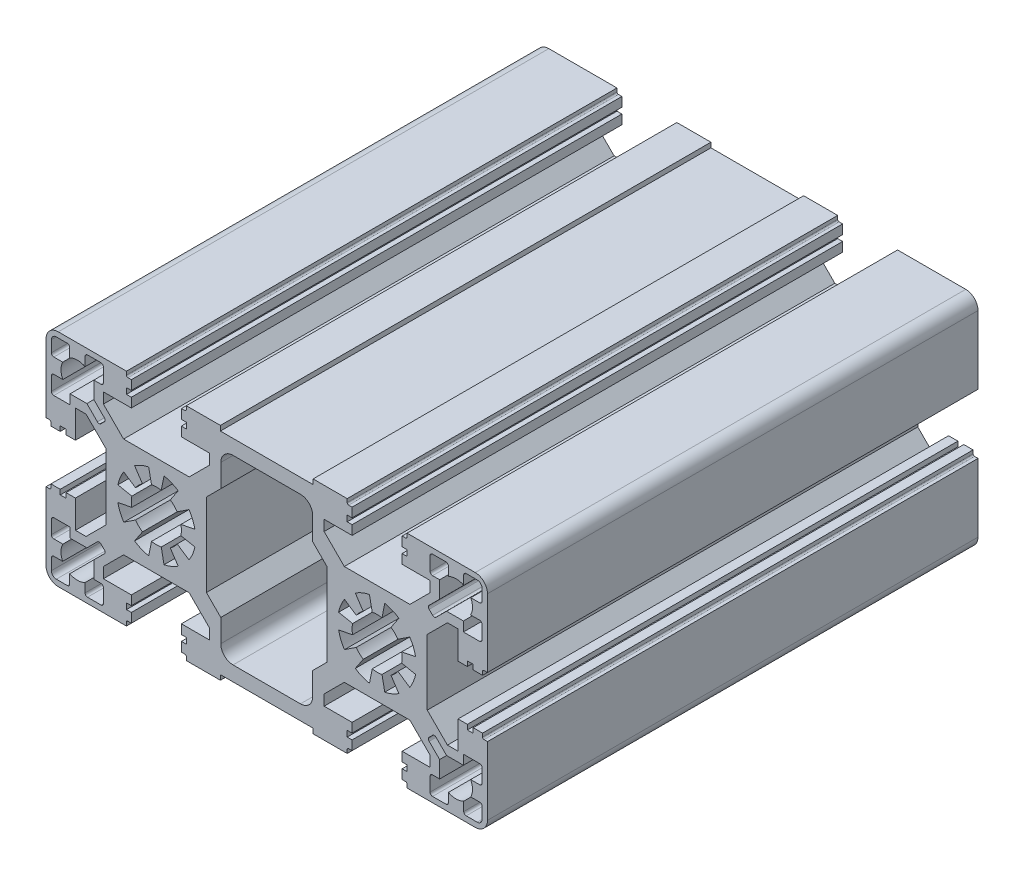
SolidWorks part; units mm, degrees
ref_plane "前视基准面" through (0, 0, 0) normal (0, 0, 1) x (1, 0, 0)
ref_plane "上视基准面" through (0, 0, 0) normal (0, 1, 0) x (1, 0, 0)
ref_plane "右视基准面" through (0, 0, 0) normal (1, 0, 0) x (0, 0, -1)
sketch "草图1" plane through (0, 0, 0) normal (0, 0, 1) x (1, 0, 0)
  line L0 (-29.3856, 22.9542) -> (-43.2856, 22.9542)
  line L1 (-45.7856, 20.4542) -> (-45.7856, 6.5542)
  line L2 (-28.3856, 16.9542) -> (-34.0856, 16.9542)
  line L3 (-39.7856, 11.2542) -> (-39.7856, 5.5542)
  line L4 (-28.3856, 21.9542) -> (-29.0856, 21.9542)
  line L5 (-29.3856, 22.2542) -> (-29.3856, 22.9542)
  line L6 (-45.7856, 6.5542) -> (-45.0856, 6.5542)
  line L7 (-44.7856, 6.2542) -> (-44.7856, 5.5542)
  line L8 (-39.7856, 11.2542) -> (-37.6211, 11.2542)
  line L9 (-42.8856, 6.5542) -> (-41.6856, 6.5542)
  line L10 (-44.7856, 5.5542) -> (-42.8856, 5.5542)
  line L11 (-41.6856, 5.5542) -> (-39.7856, 5.5542)
  line L12 (-34.0856, 16.9542) -> (-34.0856, 14.7897)
  line L13 (-29.3856, 20.0542) -> (-29.3856, 18.8542)
  line L14 (-28.3856, 21.9542) -> (-28.3856, 20.0542)
  line L15 (-28.3856, 18.8542) -> (-28.3856, 16.9542)
  line L16 (-28.3856, 18.8542) -> (-29.3856, 18.8542)
  line L17 (-28.3856, 20.0542) -> (-29.3856, 20.0542)
  line L19 (-41.6856, 5.5542) -> (-41.6856, 6.5542)
  line L20 (-42.8856, 5.5542) -> (-42.8856, 6.5542)
  line L21 (-18.1856, 16.9542) -> (-12.4856, 16.9542)
  line L22 (-18.1856, 21.9542) -> (-17.4856, 21.9542)
  line L23 (-17.1856, 22.2542) -> (-17.1856, 22.9542)
  line L24 (-12.4856, 16.9542) -> (-12.4856, 14.7897)
  line L25 (-17.1856, 20.0542) -> (-17.1856, 18.8542)
  line L26 (-18.1856, 18.8542) -> (-17.1856, 18.8542)
  line L27 (-18.1856, 20.0542) -> (-17.1856, 20.0542)
  line L28 (-18.1856, 21.9542) -> (-18.1856, 20.0542)
  line L29 (-18.1856, 18.8542) -> (-18.1856, 16.9542)
  line L30 (-29.3856, -22.0458) -> (-43.2856, -22.0458)
  line L31 (-45.7856, -19.5458) -> (-45.7856, -5.6458)
  line L32 (-28.3856, -16.0458) -> (-34.0856, -16.0458)
  line L33 (-39.7856, -10.3458) -> (-39.7856, -4.6458)
  line L34 (-28.3856, -21.0458) -> (-29.0856, -21.0458)
  line L35 (-29.3856, -21.3458) -> (-29.3856, -22.0458)
  line L36 (-45.7856, -5.6458) -> (-45.0856, -5.6458)
  line L37 (-44.7856, -5.3458) -> (-44.7856, -4.6458)
  line L38 (-39.7856, -10.3458) -> (-37.6211, -10.3458)
  line L39 (-42.8856, -5.6458) -> (-41.6856, -5.6458)
  line L40 (-44.7856, -4.6458) -> (-42.8856, -4.6458)
  line L41 (-41.6856, -4.6458) -> (-39.7856, -4.6458)
  line L42 (-34.0856, -16.0458) -> (-34.0856, -13.8813)
  line L43 (-29.3856, -19.1458) -> (-29.3856, -17.9458)
  line L44 (-28.3856, -21.0458) -> (-28.3856, -19.1458)
  line L45 (-28.3856, -17.9458) -> (-28.3856, -16.0458)
  line L46 (-28.3856, -17.9458) -> (-29.3856, -17.9458)
  line L47 (-28.3856, -19.1458) -> (-29.3856, -19.1458)
  line L49 (-41.6856, -4.6458) -> (-41.6856, -5.6458)
  line L50 (-42.8856, -4.6458) -> (-42.8856, -5.6458)
  line L51 (-18.1856, -16.0458) -> (-12.4856, -16.0458)
  line L52 (-18.1856, -21.0458) -> (-17.4856, -21.0458)
  line L53 (-17.1856, -21.3458) -> (-17.1856, -22.0458)
  line L54 (-12.4856, -16.0458) -> (-12.4856, -13.8813)
  line L55 (-17.1856, -19.1458) -> (-17.1856, -17.9458)
  line L56 (-18.1856, -17.9458) -> (-17.1856, -17.9458)
  line L57 (-18.1856, -19.1458) -> (-17.1856, -19.1458)
  line L58 (-18.1856, -21.0458) -> (-18.1856, -19.1458)
  line L59 (-18.1856, -17.9458) -> (-18.1856, -16.0458)
  line L60 (-33.5056, 7.1387) -> (-33.5056, -6.2303)
  line L61 (-29.9701, -9.7658) -> (-16.6011, -9.7658)
  line L62 (-16.6011, 10.6742) -> (-29.9701, 10.6742)
  line L63 (-27.7302, -6.1975) -> (-26.119, -3.7863)
  line L64 (-24.8463, -7.3921) -> (-24.2806, -4.5478)
  line L65 (-21.7249, -7.3921) -> (-22.2907, -4.5478)
  line L66 (-18.8411, -6.1975) -> (-20.4522, -3.7863)
  line L67 (-16.6339, -3.9904) -> (-19.0451, -2.3792)
  line L68 (-15.4393, -1.1065) -> (-18.2836, -0.5408)
  line L69 (-15.4393, 2.0149) -> (-18.2836, 1.4492)
  line L70 (-16.6339, 4.8988) -> (-19.0451, 3.2876)
  line L71 (-18.8411, 7.106) -> (-20.4522, 4.6947)
  line L72 (-21.7249, 8.3005) -> (-22.2907, 5.4562)
  line L73 (-24.8463, 8.3005) -> (-24.2806, 5.4562)
  line L74 (-27.7302, 7.106) -> (-26.119, 4.6947)
  line L75 (-29.9374, 4.8988) -> (-27.5261, 3.2876)
  line L76 (-31.1319, 2.0149) -> (-28.2876, 1.4492)
  line L77 (-31.1319, -1.1065) -> (-28.2876, -0.5408)
  line L78 (-29.9374, -3.9904) -> (-27.5261, -2.3792)
  line L79 (-34.0856, 14.7897) -> (-29.9701, 10.6742)
  line L80 (-37.6211, 11.2542) -> (-33.5056, 7.1387)
  line L81 (-12.4856, 14.7897) -> (-16.6011, 10.6742)
  line L82 (-34.0856, -13.8813) -> (-29.9701, -9.7658)
  line L83 (-37.6211, -10.3458) -> (-33.5056, -6.2303)
  line L84 (-12.4856, -13.8813) -> (-16.6011, -9.7658)
  line L86 (-44.6856, 20.8542) -> (-44.6856, 18.5542)
  line L87 (-44.1856, 18.0542) -> (-42.381, 18.0542)
  line L88 (-36.0356, 18.0542) -> (-34.5856, 18.0542)
  line L89 (-34.0856, 18.5542) -> (-34.0856, 21.3542)
  line L90 (-34.5856, 21.8542) -> (-37.3256, 21.8542)
  line L91 (-37.8256, 21.3542) -> (-37.8256, 19.5188)
  line L93 (-40.9456, 19.5188) -> (-40.9456, 21.3542)
  line L94 (-41.4456, 21.8542) -> (-43.6856, 21.8542)
  line L95 (-36.0356, 14.6184) -> (-36.0356, 18.0542)
  line L96 (-37.4498, 13.2042) -> (-35.3064, 11.0608)
  line L97 (-36.0356, 14.6184) -> (-33.8922, 12.475)
  line L98 (-34.5993, 11.0608) -> (-33.8922, 11.7679)
  line L99 (-37.4498, 13.2042) -> (-40.8856, 13.2042)
  line L100 (-42.3502, 14.9942) -> (-44.1856, 14.9942)
  line L102 (-44.6856, 14.4942) -> (-44.6856, 11.7542)
  line L103 (-44.1856, 11.2542) -> (-40.8856, 11.2542)
  line L104 (-40.8856, 13.2042) -> (-40.8856, 11.2542)
  line L122 (-36.0356, -17.1208) -> (-34.5856, -17.1208)
  line L123 (-34.0856, -17.6208) -> (-34.0856, -20.4208)
  line L124 (-34.5856, -20.9208) -> (-37.3256, -20.9208)
  line L125 (-37.8256, -20.4208) -> (-37.8256, -18.5854)
  line L126 (-40.9456, -18.5854) -> (-40.9456, -20.4208)
  line L127 (-41.4456, -20.9208) -> (-43.6856, -20.9208)
  line L128 (-44.6856, -19.9208) -> (-44.6856, -17.6208)
  line L129 (-44.1856, -17.1208) -> (-42.381, -17.1208)
  line L130 (-42.3502, -14.0608) -> (-44.1856, -14.0608)
  line L131 (-44.6856, -13.5608) -> (-44.6856, -10.8208)
  line L132 (-44.1856, -10.3208) -> (-40.8856, -10.3208)
  line L133 (-40.8856, -10.3208) -> (-40.8856, -12.2708)
  line L134 (-40.8856, -12.2708) -> (-37.4498, -12.2708)
  line L135 (-37.4498, -12.2708) -> (-35.3064, -10.1274)
  line L136 (-34.5993, -10.1274) -> (-33.8922, -10.8345)
  line L137 (-33.8922, -11.5416) -> (-36.0356, -13.685)
  line L138 (-36.0356, -13.685) -> (-36.0356, -17.1208)
  line L139 (16.6144, 16.9542) -> (10.9144, 16.9542)
  line L140 (16.6144, 21.9542) -> (15.9144, 21.9542)
  line L141 (15.6144, 22.2542) -> (15.6144, 22.9542)
  line L142 (10.9144, 16.9542) -> (10.9144, 14.7897)
  line L143 (15.6144, 20.0542) -> (15.6144, 18.8542)
  line L144 (16.6144, 21.9542) -> (16.6144, 20.0542)
  line L145 (16.6144, 18.8542) -> (16.6144, 16.9542)
  line L146 (16.6144, 18.8542) -> (15.6144, 18.8542)
  line L147 (16.6144, 20.0542) -> (15.6144, 20.0542)
  line L148 (27.8144, 22.9542) -> (41.7144, 22.9542)
  line L149 (44.2144, 20.4542) -> (44.2144, 6.5542)
  line L150 (26.8144, 16.9542) -> (32.5144, 16.9542)
  line L151 (38.2144, 11.2542) -> (38.2144, 5.5542)
  line L152 (26.8144, 21.9542) -> (27.5144, 21.9542)
  line L153 (27.8144, 22.2542) -> (27.8144, 22.9542)
  line L154 (44.2144, 6.5542) -> (43.5144, 6.5542)
  line L155 (43.2144, 6.2542) -> (43.2144, 5.5542)
  line L156 (38.2144, 11.2542) -> (36.0499, 11.2542)
  line L157 (41.3144, 6.5542) -> (40.1144, 6.5542)
  line L158 (43.2144, 5.5542) -> (41.3144, 5.5542)
  line L159 (40.1144, 5.5542) -> (38.2144, 5.5542)
  line L160 (32.5144, 16.9542) -> (32.5144, 14.7897)
  line L161 (27.8144, 20.0542) -> (27.8144, 18.8542)
  line L162 (26.8144, 18.8542) -> (27.8144, 18.8542)
  line L163 (26.8144, 20.0542) -> (27.8144, 20.0542)
  line L165 (40.1144, 5.5542) -> (40.1144, 6.5542)
  line L166 (41.3144, 5.5542) -> (41.3144, 6.5542)
  line L167 (26.8144, 21.9542) -> (26.8144, 20.0542)
  line L168 (26.8144, 18.8542) -> (26.8144, 16.9542)
  line L169 (16.6144, -16.0458) -> (10.9144, -16.0458)
  line L170 (16.6144, -21.0458) -> (15.9144, -21.0458)
  line L171 (15.6144, -21.3458) -> (15.6144, -22.0458)
  line L172 (10.9144, -16.0458) -> (10.9144, -13.8813)
  line L173 (15.6144, -19.1458) -> (15.6144, -17.9458)
  line L174 (16.6144, -21.0458) -> (16.6144, -19.1458)
  line L175 (16.6144, -17.9458) -> (16.6144, -16.0458)
  line L176 (16.6144, -17.9458) -> (15.6144, -17.9458)
  line L177 (16.6144, -19.1458) -> (15.6144, -19.1458)
  line L178 (27.8144, -22.0458) -> (41.7144, -22.0458)
  line L179 (44.2144, -19.5458) -> (44.2144, -5.6458)
  line L180 (26.8144, -16.0458) -> (32.5144, -16.0458)
  line L181 (38.2144, -10.3458) -> (38.2144, -4.6458)
  line L182 (26.8144, -21.0458) -> (27.5144, -21.0458)
  line L183 (27.8144, -21.3458) -> (27.8144, -22.0458)
  line L184 (44.2144, -5.6458) -> (43.5144, -5.6458)
  line L185 (43.2144, -5.3458) -> (43.2144, -4.6458)
  line L186 (38.2144, -10.3458) -> (36.0499, -10.3458)
  line L187 (41.3144, -5.6458) -> (40.1144, -5.6458)
  line L188 (43.2144, -4.6458) -> (41.3144, -4.6458)
  line L189 (40.1144, -4.6458) -> (38.2144, -4.6458)
  line L190 (32.5144, -16.0458) -> (32.5144, -13.8813)
  line L191 (27.8144, -19.1458) -> (27.8144, -17.9458)
  line L192 (26.8144, -17.9458) -> (27.8144, -17.9458)
  line L193 (26.8144, -19.1458) -> (27.8144, -19.1458)
  line L195 (40.1144, -4.6458) -> (40.1144, -5.6458)
  line L196 (41.3144, -4.6458) -> (41.3144, -5.6458)
  line L197 (26.8144, -21.0458) -> (26.8144, -19.1458)
  line L198 (26.8144, -17.9458) -> (26.8144, -16.0458)
  line L199 (15.0299, -9.7658) -> (28.3989, -9.7658)
  line L200 (31.9344, -6.2303) -> (31.9344, 7.1387)
  line L201 (28.3989, 10.6742) -> (15.0299, 10.6742)
  line L202 (17.2698, -6.1975) -> (18.881, -3.7863)
  line L203 (20.1537, -7.3921) -> (20.7194, -4.5478)
  line L204 (23.2751, -7.3921) -> (22.7093, -4.5478)
  line L205 (26.1589, -6.1975) -> (24.5478, -3.7863)
  line L206 (28.3661, -3.9904) -> (25.9549, -2.3792)
  line L207 (29.5607, -1.1065) -> (26.7164, -0.5408)
  line L208 (29.5607, 2.0149) -> (26.7164, 1.4492)
  line L209 (28.3661, 4.8988) -> (25.9549, 3.2876)
  line L210 (26.1589, 7.106) -> (24.5478, 4.6947)
  line L211 (23.2751, 8.3005) -> (22.7093, 5.4562)
  line L212 (20.1537, 8.3005) -> (20.7194, 5.4562)
  line L213 (17.2698, 7.106) -> (18.881, 4.6947)
  line L214 (15.0626, 4.8988) -> (17.4739, 3.2876)
  line L215 (13.8681, 2.0149) -> (16.7124, 1.4492)
  line L216 (13.8681, -1.1065) -> (16.7124, -0.5408)
  line L217 (15.0626, -3.9904) -> (17.4739, -2.3792)
  line L218 (10.9144, 14.7897) -> (15.0299, 10.6742)
  line L219 (32.5144, 14.7897) -> (28.3989, 10.6742)
  line L220 (36.0499, 11.2542) -> (31.9344, 7.1387)
  line L221 (10.9144, -13.8813) -> (15.0299, -9.7658)
  line L222 (32.5144, -13.8813) -> (28.3989, -9.7658)
  line L223 (36.0499, -10.3458) -> (31.9344, -6.2303)
  line L224 (34.4644, 18.0542) -> (33.0144, 18.0542)
  line L225 (32.5144, 18.5542) -> (32.5144, 21.3542)
  line L226 (33.0144, 21.8542) -> (35.7544, 21.8542)
  line L227 (36.2544, 21.3542) -> (36.2544, 19.5188)
  line L228 (39.3744, 19.5188) -> (39.3744, 21.3542)
  line L229 (39.8744, 21.8542) -> (42.1144, 21.8542)
  line L230 (43.1144, 20.8542) -> (43.1144, 18.5542)
  line L231 (42.6144, 18.0542) -> (40.8098, 18.0542)
  line L232 (40.779, 14.9942) -> (42.6144, 14.9942)
  line L233 (43.1144, 14.4942) -> (43.1144, 11.7542)
  line L234 (42.6144, 11.2542) -> (39.3144, 11.2542)
  line L235 (39.3144, 11.2542) -> (39.3144, 13.2042)
  line L236 (39.3144, 13.2042) -> (35.8786, 13.2042)
  line L237 (35.8786, 13.2042) -> (33.7352, 11.0608)
  line L238 (33.0281, 11.0608) -> (32.321, 11.7679)
  line L239 (32.321, 12.475) -> (34.4644, 14.6184)
  line L240 (34.4644, 14.6184) -> (34.4644, 18.0542)
  line L241 (34.4644, -17.1208) -> (33.0144, -17.1208)
  line L242 (32.5144, -17.6208) -> (32.5144, -20.4208)
  line L243 (33.0144, -20.9208) -> (35.7544, -20.9208)
  line L244 (36.2544, -20.4208) -> (36.2544, -18.5854)
  line L245 (39.3744, -18.5854) -> (39.3744, -20.4208)
  line L246 (39.8744, -20.9208) -> (42.1144, -20.9208)
  line L247 (43.1144, -19.9208) -> (43.1144, -17.6208)
  line L248 (42.6144, -17.1208) -> (40.8098, -17.1208)
  line L249 (40.779, -14.0608) -> (42.6144, -14.0608)
  line L250 (43.1144, -13.5608) -> (43.1144, -10.8208)
  line L251 (42.6144, -10.3208) -> (39.3144, -10.3208)
  line L252 (39.3144, -10.3208) -> (39.3144, -12.2708)
  line L253 (39.3144, -12.2708) -> (35.8786, -12.2708)
  line L254 (35.8786, -12.2708) -> (33.7352, -10.1274)
  line L255 (33.0281, -10.1274) -> (32.321, -10.8345)
  line L256 (32.321, -11.5416) -> (34.4644, -13.685)
  line L257 (34.4644, -13.685) -> (34.4644, -17.1208)
  line L258 (-17.1856, 22.9542) -> (-10.2356, 22.9542)
  line L259 (-10.2356, 21.9542) -> (8.6644, 21.9542)
  line L260 (-10.1562, 11.8158) -> (-10.1562, 16.4542)
  line L261 (-7.6562, 18.9542) -> (6.085, 18.9542)
  line L262 (8.585, 16.4542) -> (8.585, 11.8158)
  line L263 (-10.1562, 11.8158) -> (-13.0856, 8.8864)
  line L264 (-10.1562, -10.9074) -> (-13.0856, -7.978)
  line L265 (15.6144, 22.9542) -> (8.6644, 22.9542)
  line L266 (8.585, 11.8158) -> (11.5144, 8.8864)
  line L267 (8.585, -10.9074) -> (11.5144, -7.978)
  line L268 (-17.1856, -22.0458) -> (-10.2356, -22.0458)
  line L269 (8.6644, -22.0458) -> (15.6144, -22.0458)
  line L270 (-10.2356, -21.0458) -> (8.6644, -21.0458)
  line L271 (8.6644, -22.0458) -> (8.6644, -21.0458)
  line L272 (8.6644, 21.9542) -> (8.6644, 22.9542)
  line L273 (-10.2356, -22.0458) -> (-10.2356, -21.0458)
  line L274 (-10.2356, 21.9542) -> (-10.2356, 22.9542)
  line L275 (-13.0856, 8.8864) -> (-13.0856, -7.978)
  line L276 (11.5144, 8.8864) -> (11.5144, -7.978)
  line L277 (-10.1562, -10.9074) -> (-10.1562, -15.5458)
  line L278 (-7.6562, -18.0458) -> (6.085, -18.0458)
  line L279 (8.585, -15.5458) -> (8.585, -10.9074)
  arc A0 (-43.2856, 22.9542) -> (-45.7856, 20.4542) centre (-43.2856, 20.4542) ccw
  arc A1 (-29.3856, 22.2542) -> (-29.0856, 21.9542) centre (-29.0856, 22.2542) ccw
  arc A2 (-44.7856, 6.2542) -> (-45.0856, 6.5542) centre (-45.0856, 6.2542) ccw
  arc A3 (-17.4856, 21.9542) -> (-17.1856, 22.2542) centre (-17.4856, 22.2542) ccw
  arc A4 (-45.7856, -19.5458) -> (-43.2856, -22.0458) centre (-43.2856, -19.5458) ccw
  arc A5 (-29.0856, -21.0458) -> (-29.3856, -21.3458) centre (-29.0856, -21.3458) ccw
  arc A6 (-45.0856, -5.6458) -> (-44.7856, -5.3458) centre (-45.0856, -5.3458) ccw
  arc A7 (-17.1856, -21.3458) -> (-17.4856, -21.0458) centre (-17.4856, -21.3458) ccw
  arc A8 (-24.2806, -4.5478) -> (-22.2907, -4.5478) centre (-23.2856, 0.4542) ccw
  arc A9 (-20.4522, -3.7863) -> (-19.0451, -2.3792) centre (-23.2856, 0.4542) ccw
  arc A10 (-18.2836, -0.5408) -> (-18.2836, 1.4492) centre (-23.2856, 0.4542) ccw
  arc A11 (-19.0451, 3.2876) -> (-20.4522, 4.6947) centre (-23.2856, 0.4542) ccw
  arc A12 (-22.2907, 5.4562) -> (-24.2806, 5.4562) centre (-23.2856, 0.4542) ccw
  arc A13 (-26.119, 4.6947) -> (-27.5261, 3.2876) centre (-23.2856, 0.4542) ccw
  arc A14 (-28.2876, 1.4492) -> (-28.2876, -0.5408) centre (-23.2856, 0.4542) ccw
  arc A15 (-27.5261, -2.3792) -> (-26.119, -3.7863) centre (-23.2856, 0.4542) ccw
  arc A16 (-27.7302, -6.1975) -> (-24.8463, -7.3921) centre (-23.2856, 0.4542) ccw
  arc A17 (-21.7249, -7.3921) -> (-18.8411, -6.1975) centre (-23.2856, 0.4542) ccw
  arc A18 (-16.6339, -3.9904) -> (-15.4393, -1.1065) centre (-23.2856, 0.4542) ccw
  arc A19 (-15.4393, 2.0149) -> (-16.6339, 4.8988) centre (-23.2856, 0.4542) ccw
  arc A20 (-18.8411, 7.106) -> (-21.7249, 8.3005) centre (-23.2856, 0.4542) ccw
  arc A21 (-24.8463, 8.3005) -> (-27.7302, 7.106) centre (-23.2856, 0.4542) ccw
  arc A22 (-29.9374, 4.8988) -> (-31.1319, 2.0149) centre (-23.2856, 0.4542) ccw
  arc A23 (-31.1319, -1.1065) -> (-29.9374, -3.9904) centre (-23.2856, 0.4542) ccw
  arc A24 (-42.381, 18.0542) -> (-42.3502, 14.9942) centre (-39.3856, 16.5542) ccw
  arc A25 (-37.8256, 19.5188) -> (-40.9456, 19.5188) centre (-39.3856, 16.5542) ccw
  arc A26 (-43.6856, 21.8542) -> (-44.6856, 20.8542) centre (-43.6856, 20.8542) ccw
  arc A27 (-44.6856, 18.5542) -> (-44.1856, 18.0542) centre (-44.1856, 18.5542) ccw
  arc A28 (-34.5856, 18.0542) -> (-34.0856, 18.5542) centre (-34.5856, 18.5542) ccw
  arc A29 (-34.0856, 21.3542) -> (-34.5856, 21.8542) centre (-34.5856, 21.3542) ccw
  arc A30 (-37.3256, 21.8542) -> (-37.8256, 21.3542) centre (-37.3256, 21.3542) ccw
  arc A31 (-40.9456, 21.3542) -> (-41.4456, 21.8542) centre (-41.4456, 21.3542) ccw
  arc A32 (-35.3064, 11.0608) -> (-34.5993, 11.0608) centre (-34.9529, 11.4144) ccw
  arc A33 (-33.8922, 11.7679) -> (-33.8922, 12.475) centre (-34.2458, 12.1215) ccw
  arc A34 (-44.1856, 14.9942) -> (-44.6856, 14.4942) centre (-44.1856, 14.4942) ccw
  arc A35 (-44.6856, 11.7542) -> (-44.1856, 11.2542) centre (-44.1856, 11.7542) ccw
  arc A48 (-34.0856, -17.6208) -> (-34.5856, -17.1208) centre (-34.5856, -17.6208) ccw
  arc A49 (-34.5856, -20.9208) -> (-34.0856, -20.4208) centre (-34.5856, -20.4208) ccw
  arc A50 (-37.8256, -20.4208) -> (-37.3256, -20.9208) centre (-37.3256, -20.4208) ccw
  arc A51 (-40.9456, -18.5854) -> (-37.8256, -18.5854) centre (-39.3856, -15.6208) ccw
  arc A52 (-41.4456, -20.9208) -> (-40.9456, -20.4208) centre (-41.4456, -20.4208) ccw
  arc A53 (-44.6856, -19.9208) -> (-43.6856, -20.9208) centre (-43.6856, -19.9208) ccw
  arc A54 (-44.1856, -17.1208) -> (-44.6856, -17.6208) centre (-44.1856, -17.6208) ccw
  arc A55 (-42.3502, -14.0608) -> (-42.381, -17.1208) centre (-39.3856, -15.6208) ccw
  arc A56 (-44.6856, -13.5608) -> (-44.1856, -14.0608) centre (-44.1856, -13.5608) ccw
  arc A57 (-44.1856, -10.3208) -> (-44.6856, -10.8208) centre (-44.1856, -10.8208) ccw
  arc A58 (-34.5993, -10.1274) -> (-35.3064, -10.1274) centre (-34.9529, -10.481) ccw
  arc A59 (-33.8922, -11.5416) -> (-33.8922, -10.8345) centre (-34.2458, -11.1881) ccw
  arc A60 (15.6144, 22.2542) -> (15.9144, 21.9542) centre (15.9144, 22.2542) ccw
  arc A61 (44.2144, 20.4542) -> (41.7144, 22.9542) centre (41.7144, 20.4542) ccw
  arc A62 (27.5144, 21.9542) -> (27.8144, 22.2542) centre (27.5144, 22.2542) ccw
  arc A63 (43.5144, 6.5542) -> (43.2144, 6.2542) centre (43.5144, 6.2542) ccw
  arc A64 (15.9144, -21.0458) -> (15.6144, -21.3458) centre (15.9144, -21.3458) ccw
  arc A65 (41.7144, -22.0458) -> (44.2144, -19.5458) centre (41.7144, -19.5458) ccw
  arc A66 (27.8144, -21.3458) -> (27.5144, -21.0458) centre (27.5144, -21.3458) ccw
  arc A67 (43.2144, -5.3458) -> (43.5144, -5.6458) centre (43.5144, -5.3458) ccw
  arc A68 (20.7194, -4.5478) -> (22.7093, -4.5478) centre (21.7144, 0.4542) ccw
  arc A69 (24.5478, -3.7863) -> (25.9549, -2.3792) centre (21.7144, 0.4542) ccw
  arc A70 (26.7164, -0.5408) -> (26.7164, 1.4492) centre (21.7144, 0.4542) ccw
  arc A71 (25.9549, 3.2876) -> (24.5478, 4.6947) centre (21.7144, 0.4542) ccw
  arc A72 (22.7093, 5.4562) -> (20.7194, 5.4562) centre (21.7144, 0.4542) ccw
  arc A73 (18.881, 4.6947) -> (17.4739, 3.2876) centre (21.7144, 0.4542) ccw
  arc A74 (16.7124, 1.4492) -> (16.7124, -0.5408) centre (21.7144, 0.4542) ccw
  arc A75 (17.4739, -2.3792) -> (18.881, -3.7863) centre (21.7144, 0.4542) ccw
  arc A76 (17.2698, -6.1975) -> (20.1537, -7.3921) centre (21.7144, 0.4542) ccw
  arc A77 (23.2751, -7.3921) -> (26.1589, -6.1975) centre (21.7144, 0.4542) ccw
  arc A78 (28.3661, -3.9904) -> (29.5607, -1.1065) centre (21.7144, 0.4542) ccw
  arc A79 (29.5607, 2.0149) -> (28.3661, 4.8988) centre (21.7144, 0.4542) ccw
  arc A80 (26.1589, 7.106) -> (23.2751, 8.3005) centre (21.7144, 0.4542) ccw
  arc A81 (20.1537, 8.3005) -> (17.2698, 7.106) centre (21.7144, 0.4542) ccw
  arc A82 (15.0626, 4.8988) -> (13.8681, 2.0149) centre (21.7144, 0.4542) ccw
  arc A83 (13.8681, -1.1065) -> (15.0626, -3.9904) centre (21.7144, 0.4542) ccw
  arc A84 (32.5144, 18.5542) -> (33.0144, 18.0542) centre (33.0144, 18.5542) ccw
  arc A85 (33.0144, 21.8542) -> (32.5144, 21.3542) centre (33.0144, 21.3542) ccw
  arc A86 (36.2544, 21.3542) -> (35.7544, 21.8542) centre (35.7544, 21.3542) ccw
  arc A87 (39.3744, 19.5188) -> (36.2544, 19.5188) centre (37.8144, 16.5542) ccw
  arc A88 (39.8744, 21.8542) -> (39.3744, 21.3542) centre (39.8744, 21.3542) ccw
  arc A89 (43.1144, 20.8542) -> (42.1144, 21.8542) centre (42.1144, 20.8542) ccw
  arc A90 (42.6144, 18.0542) -> (43.1144, 18.5542) centre (42.6144, 18.5542) ccw
  arc A91 (40.779, 14.9942) -> (40.8098, 18.0542) centre (37.8144, 16.5542) ccw
  arc A92 (43.1144, 14.4942) -> (42.6144, 14.9942) centre (42.6144, 14.4942) ccw
  arc A93 (42.6144, 11.2542) -> (43.1144, 11.7542) centre (42.6144, 11.7542) ccw
  arc A94 (33.0281, 11.0608) -> (33.7352, 11.0608) centre (33.3816, 11.4144) ccw
  arc A95 (32.321, 12.475) -> (32.321, 11.7679) centre (32.6745, 12.1215) ccw
  arc A96 (33.0144, -17.1208) -> (32.5144, -17.6208) centre (33.0144, -17.6208) ccw
  arc A97 (32.5144, -20.4208) -> (33.0144, -20.9208) centre (33.0144, -20.4208) ccw
  arc A98 (35.7544, -20.9208) -> (36.2544, -20.4208) centre (35.7544, -20.4208) ccw
  arc A99 (36.2544, -18.5854) -> (39.3744, -18.5854) centre (37.8144, -15.6208) ccw
  arc A100 (39.3744, -20.4208) -> (39.8744, -20.9208) centre (39.8744, -20.4208) ccw
  arc A101 (42.1144, -20.9208) -> (43.1144, -19.9208) centre (42.1144, -19.9208) ccw
  arc A102 (43.1144, -17.6208) -> (42.6144, -17.1208) centre (42.6144, -17.6208) ccw
  arc A103 (40.8098, -17.1208) -> (40.779, -14.0608) centre (37.8144, -15.6208) ccw
  arc A104 (42.6144, -14.0608) -> (43.1144, -13.5608) centre (42.6144, -13.5608) ccw
  arc A105 (43.1144, -10.8208) -> (42.6144, -10.3208) centre (42.6144, -10.8208) ccw
  arc A106 (33.7352, -10.1274) -> (33.0281, -10.1274) centre (33.3816, -10.481) ccw
  arc A107 (32.321, -10.8345) -> (32.321, -11.5416) centre (32.6745, -11.1881) ccw
  arc A108 (-7.6562, 18.9542) -> (-10.1562, 16.4542) centre (-7.6562, 16.4542) ccw
  arc A109 (8.585, 16.4542) -> (6.085, 18.9542) centre (6.085, 16.4542) ccw
  arc A110 (-10.1562, -15.5458) -> (-7.6562, -18.0458) centre (-7.6562, -15.5458) ccw
  arc A111 (6.085, -18.0458) -> (8.585, -15.5458) centre (6.085, -15.5458) ccw
extrude "凸台-拉伸1" add sketch "草图1" along normal blind 100
